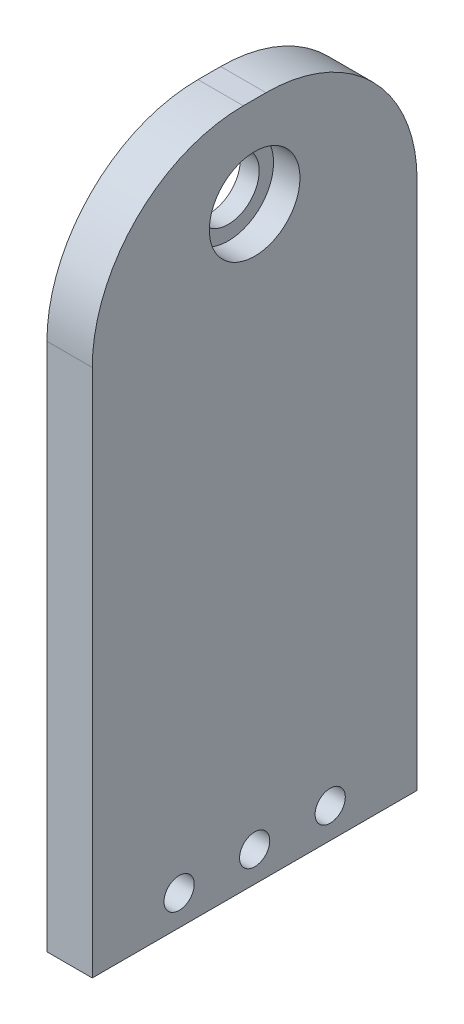
SolidWorks part; units mm, degrees
ref_plane "Front Plane" through (0, 0, 0) normal (0, 0, 1) x (1, 0, 0)
ref_plane "Top Plane" through (0, 0, 0) normal (0, 1, 0) x (1, 0, 0)
ref_plane "Right Plane" through (0, 0, 0) normal (1, 0, 0) x (0, 0, -1)
sketch "Sketch1" plane through (0, 0, 0) normal (1, 0, 0) x (0, 0, -1)
  line L1 (21.5, -45) -> (-21.5, -45)
  line L2 (21.5, -45) -> (21.5, 45)
  line L3 (21.5, 45) -> (-21.5, 45)
  line L4 (-21.5, -45) -> (-21.5, 45)
  line L5 (21.5, -45) -> (-21.5, 45) construction
  line L6 (21.5, 45) -> (-21.5, -45) construction
  point P0 (0, 0)
  dimension "D1" = 90
  dimension "D2" = 43
extrude "Boss-Extrude1" add sketch "Sketch1" along normal blind 6
sketch "Sketch2" plane through (6, 0, 0) normal (1, 0, 0) x (0, 0, -1)
  line L1 (-21.5, -45) -> (21.5, -45) construction
  line L2 (-21.5, -45) -> (-21.5, -37) construction
  line L3 (-21.5, -37) -> (21.5, -37) construction
  line L4 (21.5, -45) -> (21.5, -37) construction
  line L5 (0, -37) -> (0, -45) construction
  line L6 (-21.5, -41) -> (21.5, -41) construction
  line L7 (21.5, -45) -> (21.5, 45) construction
  circle A0 centre (0, -41) radius 2
  circle A1 centre (10, -41) radius 2
  circle A2 centre (-10, -41) radius 2
  point P196 (0, -41)
  dimension "D4" = 4
  dimension "D1" = 8
  dimension "D2" = 43
  dimension "D3" = 8
  dimension "D5" = 2
  dimension "D6" = 2
extrude "Cut-Extrude1" cut sketch "Sketch2" against normal up to next
sketch "Sketch3" plane through (6, 0, 0) normal (1, 0, 0) x (0, 0, -1)
  line L0 (-21.5, -45) -> (21.5, -45) construction
  line L1 (0, 33) -> (0, 0) construction
  circle A0 centre (0, 33) radius 4.1
  dimension "D1" = 8.2
  dimension "D2" = 78
extrude "Cut-Extrude2" cut sketch "Sketch3" against normal up to next
fillet "Fillet1" radius 20 2 edges at (3, 45, -21.5) (3, 45, 21.5)
sketch "Sketch4" plane through (6, 0, 0) normal (1, 0, 0) x (0, 0, -1)
  circle A0 centre (0, 33) radius 6
  dimension "D1" = 12
extrude "Cut-Extrude3" cut sketch "Sketch4" against normal blind 3.5
